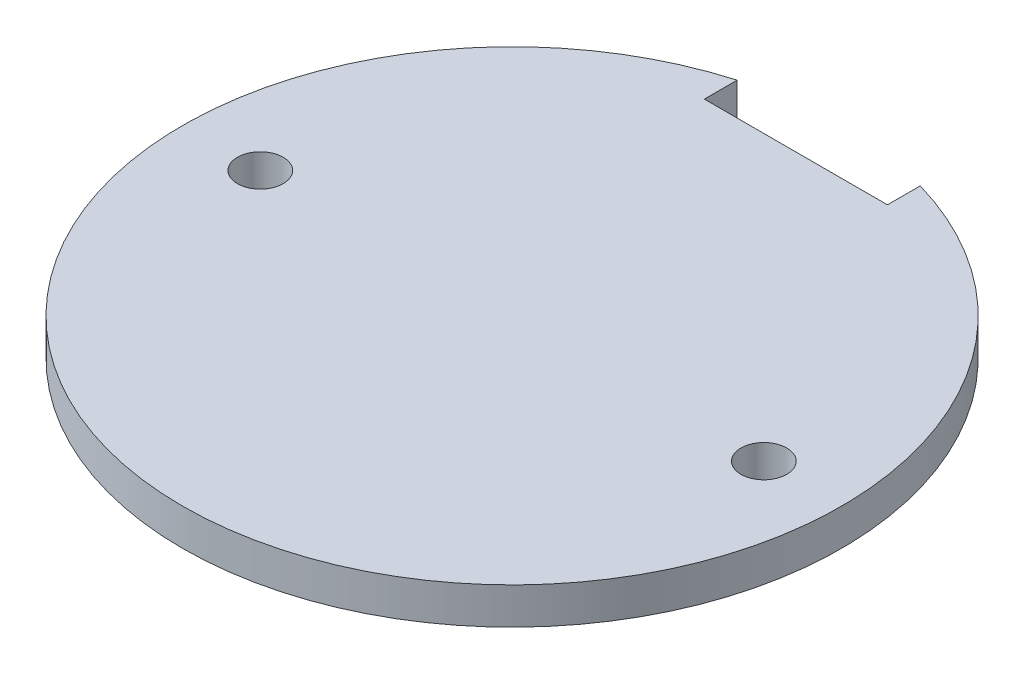
SolidWorks part; units mm, degrees
material "Balsa"
ref_plane "Front Plane" through (0, 0, 0) normal (0, 0, 1) x (1, 0, 0)
ref_plane "Top Plane" through (0, 0, 0) normal (0, 1, 0) x (1, 0, 0)
ref_plane "Right Plane" through (0, 0, 0) normal (1, 0, 0) x (0, 0, -1)
sketch "Sketch1" plane through (0, 0, 0) normal (0, 1, 0) x (1, 0, 0)
  line L0 (-36, 0) -> (36, 0) construction
  line L1 (0, 36) -> (0, -36) construction
  line L2 (-10, 34.5832) -> (-10, 31)
  line L3 (-10, 31) -> (10, 31)
  line L4 (10, 31) -> (10, 34.5832)
  arc A0 (-10, 34.5832) -> (10, 34.5832) centre (0, 0) ccw
  circle A1 centre (-27.5, 0) radius 2.5
  circle A2 centre (27.5, 0) radius 2.5
  point P1 (0, 0)
  dimension "D1" = 55
  dimension "D2" = 36
  dimension "D3" = 5
  dimension "D4" = 20
  dimension "D5" = 62
extrude "Boss-Extrude1" add sketch "Sketch1" along normal blind 4
